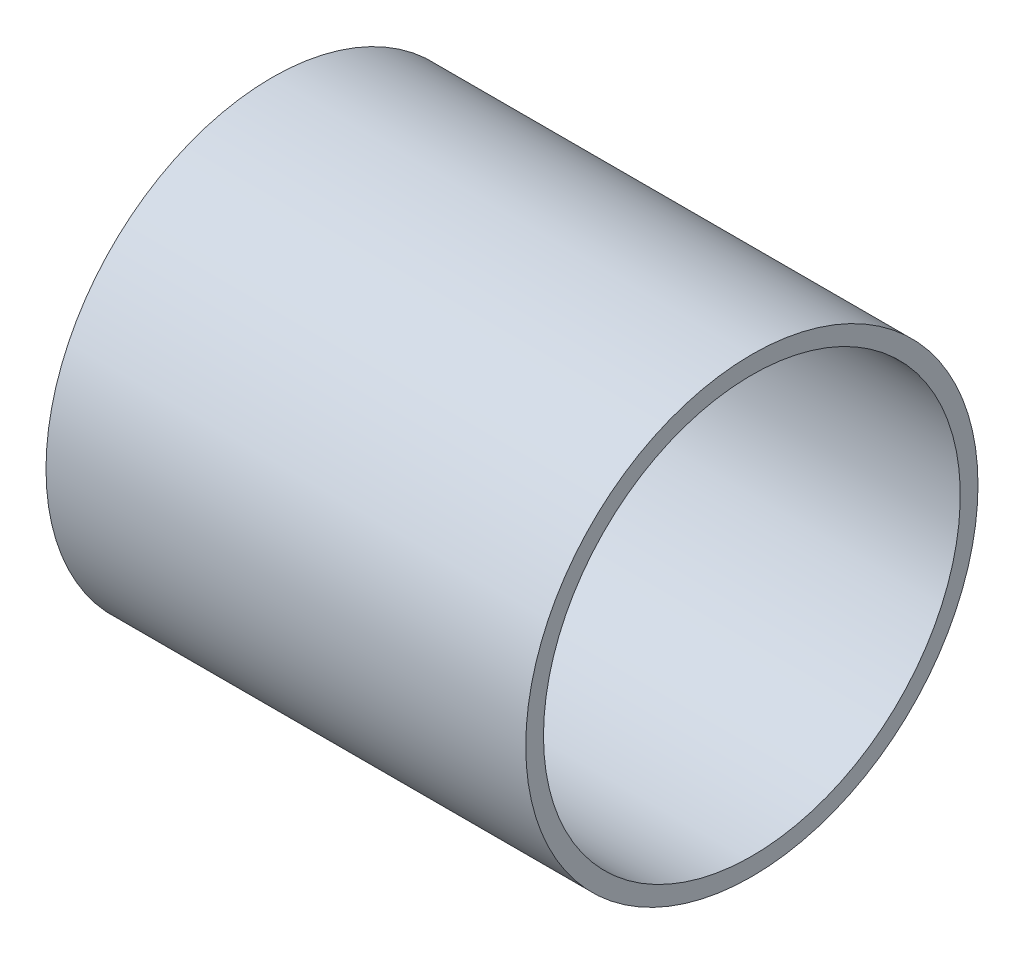
SolidWorks part; units mm, degrees
material "6061-T6 (SS)"
ref_plane "Front Plane" through (0, 0, 0) normal (0, 0, 1) x (1, 0, 0)
ref_plane "Top Plane" through (0, 0, 0) normal (0, 1, 0) x (1, 0, 0)
ref_plane "Right Plane" through (0, 0, 0) normal (1, 0, 0) x (0, 0, -1)
sketch "Sketch1" plane through (0, 0, 0) normal (0, 1, 0) x (1, 0, 0)
  line L0 (-72.894, 0) -> (78.2697, 0) construction
  line L1 (-16.8402, 15.875) -> (-16.8402, 14.6304)
  line L2 (-16.8402, 15.875) -> (16.8402, 15.875)
  line L3 (-16.8402, 14.6304) -> (16.8402, 14.6304)
  line L4 (16.8402, 15.875) -> (16.8402, 14.6304)
  line L5 (0, 0) -> (0, 14.6304) construction
  dimension "D1" = 31.75
  dimension "D2" = 1.2446
  dimension "D3" = 33.6804
revolve "Revolve1" add sketch "Sketch1" angle 360 about L0
